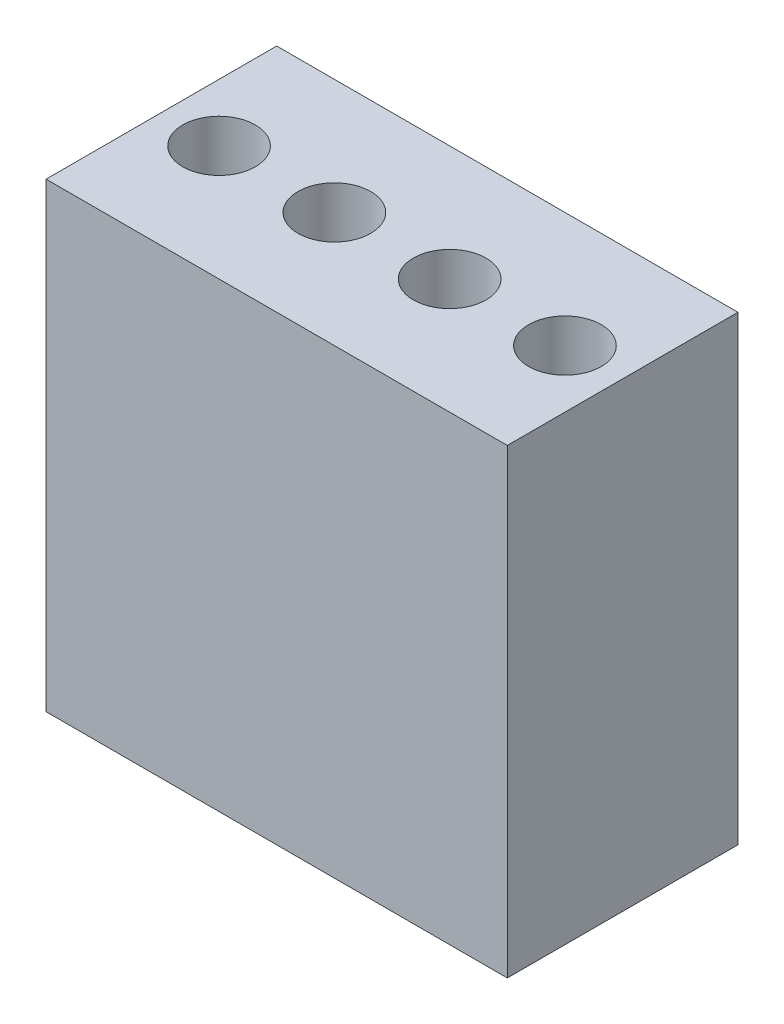
SolidWorks part; units mm, degrees
ref_plane "Front Plane" through (0, 0, 0) normal (0, 0, 1) x (1, 0, 0)
ref_plane "Top Plane" through (0, 0, 0) normal (0, 1, 0) x (1, 0, 0)
ref_plane "Right Plane" through (0, 0, 0) normal (1, 0, 0) x (0, 0, -1)
sketch "Sketch1" plane through (0, 0, 0) normal (0, 1, 0) x (1, 0, 0)
  line L0 (0, 3.175) -> (12.7, 3.175) construction
  line L1 (0, 0) -> (12.7, 0)
  line L2 (0, 0) -> (0, 6.35)
  line L3 (0, 6.35) -> (12.7, 6.35)
  line L4 (12.7, 0) -> (12.7, 6.35)
  circle A0 centre (1.5875, 3.175) radius 1
  circle A1 centre (4.7625, 3.175) radius 1
  circle A2 centre (7.9375, 3.175) radius 1
  circle A3 centre (11.1125, 3.175) radius 1
  dimension "D3" = 2
  dimension "D1" = 12.7
  dimension "D2" = 6.35
  dimension "D4" = 1.5875
  dimension "D5" = 4
extrude "Boss-Extrude1" add sketch "Sketch1" along normal blind 12.7
